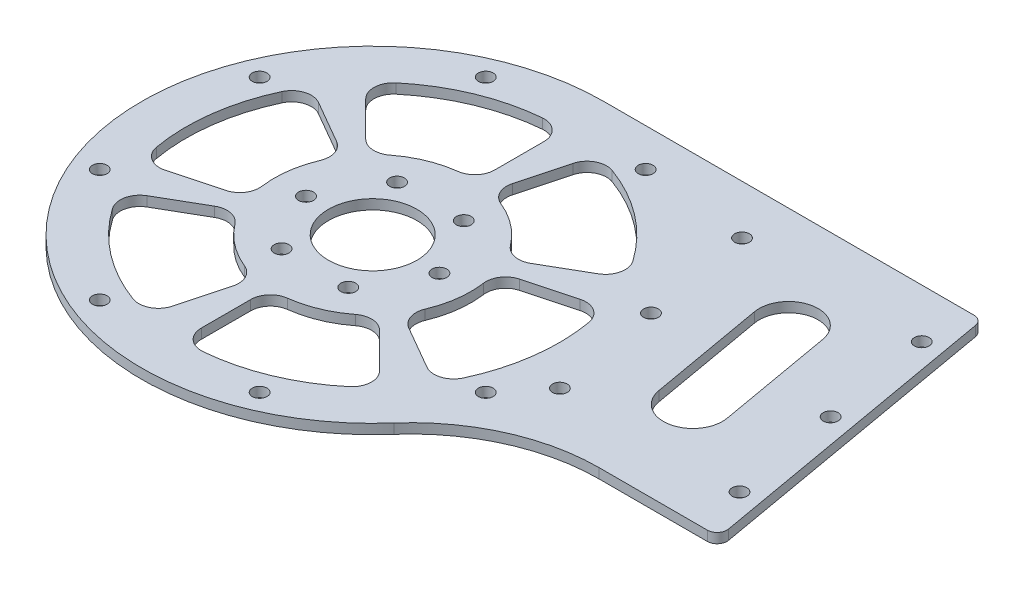
SolidWorks part; units mm, degrees
material "Hexcel AS4C (3000 丝)"
ref_plane "前视基准面" through (0, 0, 0) normal (0, 0, 1) x (1, 0, 0)
ref_plane "上视基准面" through (0, 0, 0) normal (0, 1, 0) x (1, 0, 0)
ref_plane "右视基准面" through (0, 0, 0) normal (1, 0, 0) x (0, 0, -1)
sketch "草图1" plane through (0, 0, 0) normal (0, 1, 0) x (1, 0, 0)
  line L0 (-247.6136, -26.9029) -> (538.3864, -26.9029) construction
  line L1 (0, 47) -> (75.3218, 47)
  line L2 (86.0777, -18) -> (64.0777, -18)
  line L3 (77.2914, 45.3473) -> (88.0474, -15.6527)
  line L5 (-16.264, 39.2649) -> (-39.2649, 16.264) construction
  line L6 (-39.2649, 16.264) -> (-39.2649, -16.264) construction
  line L7 (-39.2649, -16.264) -> (-16.264, -39.2649) construction
  line L8 (-16.264, -39.2649) -> (16.264, -39.2649) construction
  line L9 (16.264, -39.2649) -> (39.2649, -16.264) construction
  line L10 (39.2649, -16.264) -> (39.2649, 16.264) construction
  line L11 (39.2649, 16.264) -> (16.264, 39.2649) construction
  line L12 (16.264, 39.2649) -> (-16.264, 39.2649) construction
  line L13 (6.7839, -11.75) -> (13.5677, 0) construction
  line L14 (13.5677, 0) -> (6.7839, 11.75) construction
  line L15 (6.7839, 11.75) -> (-6.7839, 11.75) construction
  line L16 (-6.7839, 11.75) -> (-13.5677, 0) construction
  line L17 (-13.5677, 0) -> (-6.7839, -11.75) construction
  line L18 (-6.7839, -11.75) -> (6.7839, -11.75) construction
  circle A0 centre (0, 0) radius 47 construction
  arc A1 (64.0777, -18) -> (35.3098, -31.0197) centre (64.0777, -56.2924) ccw
  arc A2 (75.3218, 47) -> (77.2914, 45.3473) centre (75.3218, 45) cw
  arc A3 (86.0777, -18) -> (88.0474, -15.6527) centre (86.0777, -16) ccw
  arc A4 (0, 47) -> (35.3098, -31.0197) centre (0, 0) ccw
  circle A5 centre (0, 0) radius 42.5 construction
  circle A6 centre (-16.264, 39.2649) radius 1.5
  circle A7 centre (16.264, 39.2649) radius 1.5
  circle A8 centre (39.2649, 16.264) radius 1.5 construction
  circle A9 centre (39.2649, -16.264) radius 1.5
  circle A10 centre (16.264, -39.2649) radius 1.5
  circle A11 centre (-16.264, -39.2649) radius 1.5
  circle A12 centre (-39.2649, -16.264) radius 1.5
  circle A13 centre (-39.2649, 16.264) radius 1.5
  circle A14 centre (0, 0) radius 9
  circle A15 centre (0, 0) radius 11.75 construction
  circle A16 centre (-6.7839, 11.75) radius 1.5
  circle A17 centre (6.7839, 11.75) radius 1.5
  circle A18 centre (13.5677, 0) radius 1.5
  circle A19 centre (6.7839, -11.75) radius 1.5
  circle A20 centre (-6.7839, -11.75) radius 1.5
  circle A21 centre (-13.5677, 0) radius 1.5
  point P13 (77, 47)
  dimension "D1" = 94
  dimension "D5" = 2
  dimension "D7" = 85
  dimension "D8" = 3
  dimension "D9" = 18
  dimension "D11" = 3
  dimension "D2" = 80
  dimension "D3" = 77
  dimension "D4" = 65
  dimension "D6" = 22
  dimension "D10" = 23.5
extrude "凸台-拉伸1" add sketch "草图1" along normal blind 2
sketch "草图2" plane through (0, 2, 0) normal (0, 1, 0) x (1, 0, 0)
  line L0 (68.8766, 47) -> (116.6298, -223.8221) construction
  line L1 (68.8766, 47) -> (41.302, 42.1379) construction
  line L2 (116.6298, -223.8221) -> (89.0552, -228.6843) construction
  line L3 (41.302, 42.1379) -> (89.0552, -228.6843) construction
  line L4 (68.8766, 47) -> (89.0552, -228.6843) construction
  line L5 (116.6298, -223.8221) -> (41.302, 42.1379) construction
  line L6 (88.0474, -15.6527) -> (77.2914, 45.3473) construction
  line L7 (75.3218, 47) -> (0, 47) construction
  line L8 (74.7016, 37) -> (82.6363, -8) construction
  line L9 (64.0777, -18) -> (86.0777, -18) construction
  line L10 (78.9659, -90.8421) -> (67.6998, -26.9489) construction
  line L11 (38.1462, 37) -> (46.0809, -8) construction
  line L12 (78.6689, 14.5) -> (42.1136, 14.5) construction
  line L13 (58.3075, 26.3177) -> (62.475, 2.6823) construction
  line L14 (64.2163, 27.3596) -> (68.3839, 3.7242)
  line L15 (52.3986, 25.2758) -> (56.5662, 1.6404)
  circle A0 centre (74.7016, 37) radius 1.5
  circle A1 centre (78.6689, 14.5) radius 1.5
  circle A2 centre (82.6363, -8) radius 1.5
  circle A3 centre (38.1462, 37) radius 1.5
  circle A4 centre (46.0809, -8) radius 1.5
  circle A5 centre (42.1136, 14.5) radius 1.5
  arc A6 (64.2163, 27.3596) -> (52.3986, 25.2758) centre (58.3075, 26.3177) ccw
  arc A7 (56.5662, 1.6404) -> (68.3839, 3.7242) centre (62.475, 2.6823) ccw
  point P1 (78.9659, -90.8421)
  point P27 (60.3912, 14.5)
  dimension "D7" = 3
  dimension "D1" = 28
  dimension "D2" = 8
  dimension "D3" = 275
  dimension "D4" = 10
  dimension "D5" = 10
  dimension "D6" = 4
  dimension "D8" = 4
  dimension "D9" = 10
  dimension "D10" = 10
  dimension "D11" = 12
  dimension "D12" = 24
extrude "切除-拉伸1" cut sketch "草图2" against normal through all both and the other way through all
sketch "草图3" plane through (0, 0, 0) normal (0, -1, 0) x (1, 0, 0)
  line L2 (64.2163, -27.3596) -> (68.3839, -3.7242)
  line L3 (56.5662, -1.6404) -> (52.3986, -25.2758)
  line L4 (64.2163, -27.3596) -> (68.3839, -3.7242)
  line L5 (56.5662, -1.6404) -> (52.3986, -25.2758)
  line L6 (5.197, -23.2592) -> (7.7996, -32.9722)
  line L7 (29.83, -16.0677) -> (21.1216, -11.0399)
  line L8 (5.197, -23.2592) -> (7.7996, -32.9722)
  line L9 (29.83, -16.0677) -> (21.1216, -11.0399)
  line L10 (22.7416, -7.1289) -> (32.4546, -9.7315)
  line L11 (28.83, 17.7997) -> (20.1216, 12.7719)
  line L12 (22.7416, -7.1289) -> (32.4546, -9.7315)
  line L13 (28.83, 17.7997) -> (20.1216, 12.7719)
  line L14 (-22.7416, 7.1289) -> (-32.4546, 9.7315)
  line L15 (-28.83, -17.7997) -> (-20.1216, -12.7719)
  line L16 (-22.7416, 7.1289) -> (-32.4546, 9.7315)
  line L17 (-28.83, -17.7997) -> (-20.1216, -12.7719)
  line L18 (-17.5446, -16.1304) -> (-24.655, -23.2408)
  line L19 (1, -33.8674) -> (1, -23.8118)
  line L20 (-17.5446, -16.1304) -> (-24.655, -23.2408)
  line L21 (1, -33.8674) -> (1, -23.8118)
  line L22 (-5.197, 23.2592) -> (-7.7996, 32.9722)
  line L23 (-29.83, 16.0677) -> (-21.1216, 11.0399)
  line L24 (-5.197, 23.2592) -> (-7.7996, 32.9722)
  line L25 (-29.83, 16.0677) -> (-21.1216, 11.0399)
  line L26 (17.5446, 16.1304) -> (24.655, 23.2408)
  line L27 (-1, 33.8674) -> (-1, 23.8118)
  line L28 (17.5446, 16.1304) -> (24.655, 23.2408)
  line L29 (-1, 33.8674) -> (-1, 23.8118)
  circle A1 centre (-16.264, -39.2649) radius 1.5
  circle A2 centre (-16.264, -39.2649) radius 1.5
  circle A3 centre (16.264, -39.2649) radius 1.5
  circle A4 centre (16.264, -39.2649) radius 1.5
  circle A5 centre (39.2649, 16.264) radius 1.5
  circle A6 centre (39.2649, 16.264) radius 1.5
  circle A7 centre (16.264, 39.2649) radius 1.5
  circle A8 centre (16.264, 39.2649) radius 1.5
  circle A9 centre (-16.264, 39.2649) radius 1.5
  circle A10 centre (-16.264, 39.2649) radius 1.5
  circle A11 centre (-39.2649, 16.264) radius 1.5
  circle A12 centre (-39.2649, 16.264) radius 1.5
  circle A13 centre (-39.2649, -16.264) radius 1.5
  circle A14 centre (-39.2649, -16.264) radius 1.5
  circle A15 centre (0, 0) radius 9
  circle A16 centre (0, 0) radius 9
  circle A17 centre (6.7839, -11.75) radius 1.5
  circle A18 centre (6.7839, -11.75) radius 1.5
  circle A19 centre (-6.7839, -11.75) radius 1.5
  circle A20 centre (-6.7839, -11.75) radius 1.5
  circle A21 centre (13.5677, 0) radius 1.5
  circle A22 centre (13.5677, 0) radius 1.5
  circle A23 centre (6.7839, 11.75) radius 1.5
  circle A24 centre (6.7839, 11.75) radius 1.5
  circle A25 centre (-6.7839, 11.75) radius 1.5
  circle A26 centre (-6.7839, 11.75) radius 1.5
  circle A27 centre (-13.5677, 0) radius 1.5
  circle A28 centre (-13.5677, 0) radius 1.5
  circle A29 centre (0, -13.8564) radius 2
  circle A30 centre (0, -13.8564) radius 2
  circle A31 centre (-12, 6.9282) radius 2
  circle A32 centre (-12, 6.9282) radius 2
  circle A33 centre (12, 6.9282) radius 2
  circle A34 centre (12, 6.9282) radius 2
  circle A35 centre (74.7016, -37) radius 1.5
  circle A36 centre (74.7016, -37) radius 1.5
  circle A37 centre (42.1136, -14.5) radius 1.5
  arc A38 (52.3986, -25.2758) -> (64.2163, -27.3596) centre (58.3075, -26.3177) ccw
  arc A39 (68.3839, -3.7242) -> (56.5662, -1.6404) centre (62.475, -2.6823) ccw
  arc A40 (52.3986, -25.2758) -> (64.2163, -27.3596) centre (58.3075, -26.3177) ccw
  arc A41 (68.3839, -3.7242) -> (56.5662, -1.6404) centre (62.475, -2.6823) ccw
  circle A42 centre (42.1136, -14.5) radius 1.5
  circle A43 centre (46.0809, 8) radius 1.5
  circle A44 centre (46.0809, 8) radius 1.5
  circle A45 centre (38.1462, -37) radius 1.5
  circle A46 centre (38.1462, -37) radius 1.5
  circle A47 centre (82.6363, 8) radius 1.5
  circle A48 centre (82.6363, 8) radius 1.5
  circle A49 centre (78.6689, -14.5) radius 1.5
  circle A50 centre (78.6689, -14.5) radius 1.5
  arc A56 (21.1216, -11.0399) -> (15.9347, -12.0866) centre (19.1216, -14.504) ccw
  arc A57 (7.5506, -18.5199) -> (15.9347, -12.0866) centre (0, 0) ccw
  arc A58 (7.5506, -18.5199) -> (5.197, -23.2592) centre (9.0607, -22.2239) ccw
  arc A59 (7.7996, -32.9722) -> (13.0355, -35.6942) centre (11.6633, -31.9369) ccw
  arc A60 (13.0355, -35.6942) -> (31.1041, -21.8296) centre (0, 0) ccw
  arc A61 (31.1041, -21.8296) -> (29.83, -16.0677) centre (27.83, -19.5318) ccw
  arc A62 (21.1216, -11.0399) -> (15.9347, -12.0866) centre (19.1216, -14.504) ccw
  arc A63 (7.5506, -18.5199) -> (15.9347, -12.0866) centre (0, 0) ccw
  arc A64 (7.5506, -18.5199) -> (5.197, -23.2592) centre (9.0607, -22.2239) ccw
  arc A65 (7.7996, -32.9722) -> (13.0355, -35.6942) centre (11.6633, -31.9369) ccw
  arc A66 (13.0355, -35.6942) -> (31.1041, -21.8296) centre (0, 0) ccw
  arc A67 (31.1041, -21.8296) -> (29.83, -16.0677) centre (27.83, -19.5318) ccw
  arc A68 (20.1216, 12.7719) -> (18.4347, 7.7565) centre (22.1216, 9.3078) ccw
  arc A69 (19.814, -2.721) -> (18.4347, 7.7565) centre (0, 0) ccw
  arc A70 (19.814, -2.721) -> (22.7416, -7.1289) centre (23.7769, -3.2652) ccw
  arc A71 (32.4546, -9.7315) -> (37.4298, -6.5581) centre (33.4898, -5.8677) ccw
  arc A72 (37.4298, -6.5581) -> (34.4571, 16.0222) centre (0, 0) ccw
  arc A73 (34.4571, 16.0222) -> (28.83, 17.7997) centre (30.83, 14.3356) ccw
  arc A74 (20.1216, 12.7719) -> (18.4347, 7.7565) centre (22.1216, 9.3078) ccw
  arc A75 (19.814, -2.721) -> (18.4347, 7.7565) centre (0, 0) ccw
  arc A76 (19.814, -2.721) -> (22.7416, -7.1289) centre (23.7769, -3.2652) ccw
  arc A77 (32.4546, -9.7315) -> (37.4298, -6.5581) centre (33.4898, -5.8677) ccw
  arc A78 (37.4298, -6.5581) -> (34.4571, 16.0222) centre (0, 0) ccw
  arc A79 (34.4571, 16.0222) -> (28.83, 17.7997) centre (30.83, 14.3356) ccw
  arc A80 (-20.1216, -12.7719) -> (-18.4347, -7.7565) centre (-22.1216, -9.3078) ccw
  arc A81 (-19.814, 2.721) -> (-18.4347, -7.7565) centre (0, 0) ccw
  arc A82 (-19.814, 2.721) -> (-22.7416, 7.1289) centre (-23.7769, 3.2652) ccw
  arc A83 (-32.4546, 9.7315) -> (-37.4298, 6.5581) centre (-33.4898, 5.8677) ccw
  arc A84 (-37.4298, 6.5581) -> (-34.4571, -16.0222) centre (0, 0) ccw
  arc A85 (-34.4571, -16.0222) -> (-28.83, -17.7997) centre (-30.83, -14.3356) ccw
  arc A86 (-20.1216, -12.7719) -> (-18.4347, -7.7565) centre (-22.1216, -9.3078) ccw
  arc A87 (-19.814, 2.721) -> (-18.4347, -7.7565) centre (0, 0) ccw
  arc A88 (-19.814, 2.721) -> (-22.7416, 7.1289) centre (-23.7769, 3.2652) ccw
  arc A89 (-32.4546, 9.7315) -> (-37.4298, 6.5581) centre (-33.4898, 5.8677) ccw
  arc A90 (-37.4298, 6.5581) -> (-34.4571, -16.0222) centre (0, 0) ccw
  arc A91 (-34.4571, -16.0222) -> (-28.83, -17.7997) centre (-30.83, -14.3356) ccw
  arc A92 (1, -23.8118) -> (-2.5, -19.8431) centre (-3, -23.8118) ccw
  arc A93 (-12.2634, -15.799) -> (-2.5, -19.8431) centre (0, 0) ccw
  arc A94 (-12.2634, -15.799) -> (-17.5446, -16.1304) centre (-14.7161, -18.9588) ccw
  arc A95 (-24.655, -23.2408) -> (-24.3944, -29.1361) centre (-21.8265, -26.0692) ccw
  arc A96 (-24.3944, -29.1361) -> (-3.3529, -37.8518) centre (0, 0) ccw
  arc A97 (-3.3529, -37.8518) -> (1, -33.8674) centre (-3, -33.8674) ccw
  arc A98 (1, -23.8118) -> (-2.5, -19.8431) centre (-3, -23.8118) ccw
  arc A99 (-12.2634, -15.799) -> (-2.5, -19.8431) centre (0, 0) ccw
  arc A100 (-12.2634, -15.799) -> (-17.5446, -16.1304) centre (-14.7161, -18.9588) ccw
  arc A101 (-24.655, -23.2408) -> (-24.3944, -29.1361) centre (-21.8265, -26.0692) ccw
  arc A102 (-24.3944, -29.1361) -> (-3.3529, -37.8518) centre (0, 0) ccw
  arc A103 (-3.3529, -37.8518) -> (1, -33.8674) centre (-3, -33.8674) ccw
  arc A104 (-21.1216, 11.0399) -> (-15.9347, 12.0866) centre (-19.1216, 14.504) ccw
  arc A105 (-7.5506, 18.5199) -> (-15.9347, 12.0866) centre (0, 0) ccw
  arc A106 (-7.5506, 18.5199) -> (-5.197, 23.2592) centre (-9.0607, 22.2239) ccw
  arc A107 (-7.7996, 32.9722) -> (-13.0355, 35.6942) centre (-11.6633, 31.9369) ccw
  arc A108 (-13.0355, 35.6942) -> (-31.1041, 21.8296) centre (0, 0) ccw
  arc A109 (-31.1041, 21.8296) -> (-29.83, 16.0677) centre (-27.83, 19.5318) ccw
  arc A110 (-21.1216, 11.0399) -> (-15.9347, 12.0866) centre (-19.1216, 14.504) ccw
  arc A111 (-7.5506, 18.5199) -> (-15.9347, 12.0866) centre (0, 0) ccw
  arc A112 (-7.5506, 18.5199) -> (-5.197, 23.2592) centre (-9.0607, 22.2239) ccw
  arc A113 (-7.7996, 32.9722) -> (-13.0355, 35.6942) centre (-11.6633, 31.9369) ccw
  arc A114 (-13.0355, 35.6942) -> (-31.1041, 21.8296) centre (0, 0) ccw
  arc A115 (-31.1041, 21.8296) -> (-29.83, 16.0677) centre (-27.83, 19.5318) ccw
  arc A116 (-1, 23.8118) -> (2.5, 19.8431) centre (3, 23.8118) ccw
  arc A117 (12.2634, 15.799) -> (2.5, 19.8431) centre (0, 0) ccw
  arc A118 (12.2634, 15.799) -> (17.5446, 16.1304) centre (14.7161, 18.9588) ccw
  arc A119 (24.655, 23.2408) -> (24.3944, 29.1361) centre (21.8265, 26.0692) ccw
  arc A120 (24.3944, 29.1361) -> (3.3529, 37.8518) centre (0, 0) ccw
  arc A121 (3.3529, 37.8518) -> (-1, 33.8674) centre (3, 33.8674) ccw
  arc A122 (-1, 23.8118) -> (2.5, 19.8431) centre (3, 23.8118) ccw
  arc A123 (12.2634, 15.799) -> (2.5, 19.8431) centre (0, 0) ccw
  arc A124 (12.2634, 15.799) -> (17.5446, 16.1304) centre (14.7161, 18.9588) ccw
  arc A125 (24.655, 23.2408) -> (24.3944, 29.1361) centre (21.8265, 26.0692) ccw
  arc A126 (24.3944, 29.1361) -> (3.3529, 37.8518) centre (0, 0) ccw
  arc A127 (3.3529, 37.8518) -> (-1, 33.8674) centre (3, 33.8674) ccw
  dimension "D1" = 0
  dimension "D2" = 0
  dimension "D3" = 0
  dimension "D4" = 0
  dimension "D5" = 0
  dimension "D6" = 0
  dimension "D7" = 0
  dimension "D8" = 0
  dimension "D9" = 0
  dimension "D10" = 0
  dimension "D11" = 0
  dimension "D12" = 0
  dimension "D13" = 0
  dimension "D14" = 0
  dimension "D15" = 0
  dimension "D16" = 0
  dimension "D17" = 0
  dimension "D18" = 0
  dimension "D19" = 0
  dimension "D20" = 0
  dimension "D21" = 0
  dimension "D22" = 0
  dimension "D23" = 0
  dimension "D24" = 0
  dimension "D25" = 0
  dimension "D26" = 0
  dimension "D27" = 0
  dimension "D28" = 0
  dimension "D29" = 0
  dimension "D30" = 0
extrude "切除-拉伸2" cut sketch "草图3" against normal through all both and the other way through all contours A66 A67 L9 A62 A63 A64 L8 A65 | A78 A79 L13 A74 A75 A76 L12 A77 | A126 A127 L29 A122 A123 A124 L28 A125 | A114 A115 L25 A110 A111 A112 L24 A113 | A90 A91 L17 A86 A87 A88 L16 A89 | A102 A103 L21 A98 A99 A100 L20 A101
